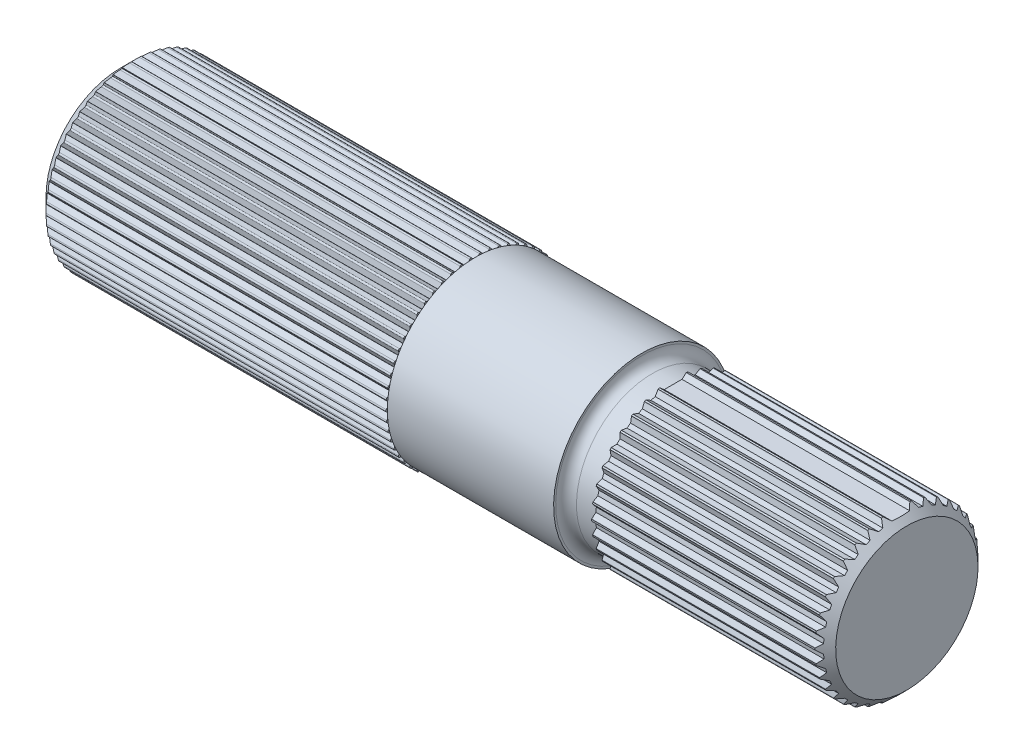
SolidWorks part; units mm, degrees
material "1.0725 (15SMn13)"
ref_plane "Ön Düzlem" through (0, 0, 0) normal (0, 0, 1) x (1, 0, 0)
ref_plane "Üst Düzlem" through (0, 0, 0) normal (0, 1, 0) x (1, 0, 0)
ref_plane "Sağ Düzlem" through (0, 0, 0) normal (1, 0, 0) x (0, 0, -1)
sketch "Çizim1" plane through (0, 0, 0) normal (0, 0, 1) x (1, 0, 0)
  line L0 (0, 0) -> (75.7, 0)
  line L1 (53.2, -7.3) -> (53.2, -7.85)
  line L2 (53.2, -7.85) -> (74.7, -7.85)
  line L3 (74.7, -7.85) -> (75.7, -6.85)
  line L4 (75.7, -6.85) -> (75.7, 0)
  line L5 (0, 0) -> (0, -7.16)
  line L6 (0, -7.16) -> (1.5, -8.66)
  line L7 (1.5, -8.66) -> (34.2, -8.66)
  line L8 (34.2, -8.66) -> (34.2, -8.5)
  line L9 (34.2, -8.5) -> (50.2, -8.5)
  line L10 (50.2, -8.5) -> (50.2, -8.3)
  line L11 (51.2, -7.3) -> (53.2, -7.3)
  arc A0 (51.2, -7.3) -> (50.2, -8.3) centre (51.2, -8.3) ccw
revolve "Döndür1" add sketch "Çizim1" angle 360 about L0
sketch "Çizim2" plane through (75.7, 0, 0) normal (1, 0, 0) x (0, 0, -1)
  line L0 (5.9329, 5.1084) -> (5.4037, 5.1084)
  line L1 (5.1084, 5.9329) -> (5.1084, 5.4037)
  line L2 (6.7298, 4.0006) -> (6.2087, 4.0925)
  line L3 (6.061, 4.9557) -> (5.9692, 4.4346)
  line L4 (7.6922, 1.4576) -> (7.234, 1.7221)
  line L5 (7.3904, 2.5838) -> (7.1259, 2.1256)
  line L6 (7.3222, 2.7712) -> (6.825, 2.9521)
  line L7 (6.8295, 3.8279) -> (6.6485, 3.3307)
  line L8 (7.8285, 0.0997) -> (7.4231, 0.4398)
  line L9 (7.7268, -1.2612) -> (7.3867, -0.8559)
  line L10 (7.8285, -0.0997) -> (7.4231, -0.4398)
  line L11 (6.8295, -3.8279) -> (6.6485, -3.3307)
  line L12 (6.7298, -4.0006) -> (6.2087, -4.0925)
  line L13 (7.3222, -2.7712) -> (6.825, -2.9521)
  line L14 (7.3904, -2.5838) -> (7.1259, -2.1256)
  line L15 (7.6922, -1.4576) -> (7.234, -1.7221)
  line L16 (6.061, -4.9557) -> (5.9692, -4.4346)
  line L17 (5.9329, -5.1084) -> (5.4037, -5.1084)
  line L18 (5.1084, -5.9329) -> (5.1084, -5.4037)
  line L19 (7.7268, 1.2612) -> (7.3867, 0.8559)
  line L20 (3.8279, 6.8295) -> (3.3307, 6.6485)
  line L21 (2.5838, 7.3904) -> (2.1256, 7.1259)
  line L22 (1.2612, 7.7268) -> (0.8559, 7.3867)
  line L23 (1.4576, 7.6922) -> (1.7221, 7.234)
  line L24 (2.7712, 7.3222) -> (2.9521, 6.825)
  line L25 (-1.2612, 7.7268) -> (-0.8559, 7.3867)
  line L26 (-2.5838, 7.3904) -> (-2.1256, 7.1259)
  line L27 (-2.7712, 7.3222) -> (-2.9521, 6.825)
  line L28 (-1.4576, 7.6922) -> (-1.7221, 7.234)
  line L29 (-0.8559, 7.3867) -> (0.8559, 7.3867)
  line L30 (4.9557, 6.061) -> (4.4346, 5.9692)
  line L31 (4.0006, 6.7298) -> (4.0925, 6.2087)
  line L32 (-5.9329, 5.1084) -> (-5.4037, 5.1084)
  line L33 (-5.1084, 5.9329) -> (-5.1084, 5.4037)
  line L34 (-4.9557, 6.061) -> (-4.4346, 5.9692)
  line L35 (-6.7298, 4.0006) -> (-6.2087, 4.0925)
  line L36 (-6.061, 4.9557) -> (-5.9692, 4.4346)
  line L37 (-7.3222, 2.7712) -> (-6.825, 2.9521)
  line L38 (-7.6922, 1.4576) -> (-7.234, 1.7221)
  line L39 (-7.3904, 2.5838) -> (-7.1259, 2.1256)
  line L40 (-6.8295, 3.8279) -> (-6.6485, 3.3307)
  line L41 (-4.0006, 6.7298) -> (-4.0925, 6.2087)
  line L42 (-3.8279, 6.8295) -> (-3.3307, 6.6485)
  line L43 (4.9557, -6.061) -> (4.4346, -5.9692)
  line L44 (2.5838, -7.3904) -> (2.1256, -7.1259)
  line L45 (1.2612, -7.7268) -> (0.8559, -7.3867)
  line L46 (1.4576, -7.6922) -> (1.7221, -7.234)
  line L47 (2.7712, -7.3222) -> (2.9521, -6.825)
  line L48 (4.0006, -6.7298) -> (4.0925, -6.2087)
  line L49 (3.8279, -6.8295) -> (3.3307, -6.6485)
  line L50 (0.0997, -7.8285) -> (0.4398, -7.4231)
  line L51 (-0.0997, -7.8285) -> (-0.4398, -7.4231)
  line L52 (-1.2612, -7.7268) -> (-0.8559, -7.3867)
  line L53 (-2.5838, -7.3904) -> (-2.1256, -7.1259)
  line L54 (-2.7712, -7.3222) -> (-2.9521, -6.825)
  line L55 (-1.4576, -7.6922) -> (-1.7221, -7.234)
  line L56 (-7.8285, 0.0997) -> (-7.4231, 0.4398)
  line L57 (-7.7268, -1.2612) -> (-7.3867, -0.8559)
  line L58 (-7.8285, -0.0997) -> (-7.4231, -0.4398)
  line L59 (-7.3904, -2.5838) -> (-7.1259, -2.1256)
  line L60 (-6.8295, -3.8279) -> (-6.6485, -3.3307)
  line L61 (-6.7298, -4.0006) -> (-6.2087, -4.0925)
  line L62 (-7.3222, -2.7712) -> (-6.825, -2.9521)
  line L63 (-7.6922, -1.4576) -> (-7.234, -1.7221)
  line L64 (-5.9329, -5.1084) -> (-5.4037, -5.1084)
  line L65 (-4.9557, -6.061) -> (-4.4346, -5.9692)
  line L66 (-5.1084, -5.9329) -> (-5.1084, -5.4037)
  line L67 (-6.061, -4.9557) -> (-5.9692, -4.4346)
  line L68 (-4.0006, -6.7298) -> (-4.0925, -6.2087)
  line L69 (-3.8279, -6.8295) -> (-3.3307, -6.6485)
  line L70 (4.0811, -6.273) -> (-4.0811, -6.273) construction
  line L71 (-7.7268, 1.2612) -> (-7.3867, 0.8559)
  arc A0 (5.4037, 5.1084) -> (5.1084, 5.4037) centre (0, 0) ccw
  arc A1 (6.8295, 3.8279) -> (6.7298, 4.0006) centre (6.7072, 3.8724) ccw
  arc A2 (6.2087, 4.0925) -> (5.9692, 4.4346) centre (0, 0) ccw
  arc A3 (6.061, 4.9557) -> (5.9329, 5.1084) centre (5.9329, 4.9783) ccw
  arc A4 (7.3904, 2.5838) -> (7.3222, 2.7712) centre (7.2777, 2.6489) ccw
  arc A5 (7.7268, 1.2612) -> (7.6922, 1.4576) centre (7.6271, 1.3449) ccw
  arc A6 (6.825, 2.9521) -> (6.6485, 3.3307) centre (0, 0) ccw
  arc A7 (7.234, 1.7221) -> (7.1259, 2.1256) centre (0, 0) ccw
  arc A8 (7.8285, -0.0997) -> (7.8285, 0.0997) centre (7.7448, 0) ccw
  arc A9 (7.4231, 0.4398) -> (7.3867, 0.8559) centre (0, 0) ccw
  arc A10 (7.3867, -0.8559) -> (7.4231, -0.4398) centre (0, 0) ccw
  arc A11 (7.6922, -1.4576) -> (7.7268, -1.2612) centre (7.6271, -1.3449) ccw
  arc A12 (7.3222, -2.7712) -> (7.3904, -2.5838) centre (7.2777, -2.6489) ccw
  arc A13 (7.1259, -2.1256) -> (7.234, -1.7221) centre (0, 0) ccw
  arc A14 (6.7298, -4.0006) -> (6.8295, -3.8279) centre (6.7072, -3.8724) ccw
  arc A15 (6.6485, -3.3307) -> (6.825, -2.9521) centre (0, 0) ccw
  arc A16 (5.1084, -5.4037) -> (5.4037, -5.1084) centre (0, 0) ccw
  arc A17 (5.9329, -5.1084) -> (6.061, -4.9557) centre (5.9329, -4.9783) ccw
  arc A18 (5.9692, -4.4346) -> (6.2087, -4.0925) centre (0, 0) ccw
  arc A19 (3.3307, 6.6485) -> (2.9521, 6.825) centre (0, 0) ccw
  arc A20 (4.0006, 6.7298) -> (3.8279, 6.8295) centre (3.8724, 6.7072) ccw
  arc A21 (1.4576, 7.6922) -> (1.2612, 7.7268) centre (1.3449, 7.6271) ccw
  arc A22 (2.7712, 7.3222) -> (2.5838, 7.3904) centre (2.6489, 7.2777) ccw
  arc A23 (2.1256, 7.1259) -> (1.7221, 7.234) centre (0, 0) ccw
  arc A24 (-1.2612, 7.7268) -> (-1.4576, 7.6922) centre (-1.3449, 7.6271) ccw
  arc A25 (-1.7221, 7.234) -> (-2.1256, 7.1259) centre (0, 0) ccw
  arc A26 (-2.9521, 6.825) -> (-3.3307, 6.6485) centre (0, 0) ccw
  arc A27 (-2.5838, 7.3904) -> (-2.7712, 7.3222) centre (-2.6489, 7.2777) ccw
  arc A28 (4.4346, 5.9692) -> (4.0925, 6.2087) centre (0, 0) ccw
  arc A29 (-3.8279, 6.8295) -> (-4.0006, 6.7298) centre (-3.8724, 6.7072) ccw
  arc A30 (-4.0925, 6.2087) -> (-4.4346, 5.9692) centre (0, 0) ccw
  arc A31 (-5.1084, 5.4037) -> (-5.4037, 5.1084) centre (0, 0) ccw
  arc A32 (-4.9557, 6.061) -> (-5.1084, 5.9329) centre (-4.9783, 5.9329) ccw
  arc A33 (-6.7298, 4.0006) -> (-6.8295, 3.8279) centre (-6.7072, 3.8724) ccw
  arc A34 (-5.9329, 5.1084) -> (-6.061, 4.9557) centre (-5.9329, 4.9783) ccw
  arc A35 (-5.9692, 4.4346) -> (-6.2087, 4.0925) centre (0, 0) ccw
  arc A36 (-6.6485, 3.3307) -> (-6.825, 2.9521) centre (0, 0) ccw
  arc A37 (-7.3222, 2.7712) -> (-7.3904, 2.5838) centre (-7.2777, 2.6489) ccw
  arc A38 (-7.1259, 2.1256) -> (-7.234, 1.7221) centre (0, 0) ccw
  arc A39 (-7.6922, 1.4576) -> (-7.7268, 1.2612) centre (-7.6271, 1.3449) ccw
  arc A40 (4.0925, -6.2087) -> (4.4346, -5.9692) centre (0, 0) ccw
  arc A41 (3.8279, -6.8295) -> (4.0006, -6.7298) centre (3.8724, -6.7072) ccw
  arc A42 (2.5838, -7.3904) -> (2.7712, -7.3222) centre (2.6489, -7.2777) ccw
  arc A43 (1.2612, -7.7268) -> (1.4576, -7.6922) centre (1.3449, -7.6271) ccw
  arc A44 (1.7221, -7.234) -> (2.1256, -7.1259) centre (0, 0) ccw
  arc A45 (2.9521, -6.825) -> (3.3307, -6.6485) centre (0, 0) ccw
  arc A46 (-0.0997, -7.8285) -> (0.0997, -7.8285) centre (0, -7.7448) ccw
  arc A47 (-1.4576, -7.6922) -> (-1.2612, -7.7268) centre (-1.3449, -7.6271) ccw
  arc A48 (-0.8559, -7.3867) -> (-0.4398, -7.4231) centre (0, 0) ccw
  arc A49 (-2.1256, -7.1259) -> (-1.7221, -7.234) centre (0, 0) ccw
  arc A50 (-2.7712, -7.3222) -> (-2.5838, -7.3904) centre (-2.6489, -7.2777) ccw
  arc A51 (-3.3307, -6.6485) -> (-2.9521, -6.825) centre (0, 0) ccw
  arc A52 (0.4398, -7.4231) -> (0.8559, -7.3867) centre (0, 0) ccw
  arc A53 (-7.8285, 0.0997) -> (-7.8285, -0.0997) centre (-7.7448, 0) ccw
  arc A54 (-7.3867, 0.8559) -> (-7.4231, 0.4398) centre (0, 0) ccw
  arc A55 (-7.4231, -0.4398) -> (-7.3867, -0.8559) centre (0, 0) ccw
  arc A56 (-7.7268, -1.2612) -> (-7.6922, -1.4576) centre (-7.6271, -1.3449) ccw
  arc A57 (-7.3904, -2.5838) -> (-7.3222, -2.7712) centre (-7.2777, -2.6489) ccw
  arc A58 (-7.234, -1.7221) -> (-7.1259, -2.1256) centre (0, 0) ccw
  arc A59 (-6.825, -2.9521) -> (-6.6485, -3.3307) centre (0, 0) ccw
  arc A60 (-6.8295, -3.8279) -> (-6.7298, -4.0006) centre (-6.7072, -3.8724) ccw
  arc A61 (-5.4037, -5.1084) -> (-5.1084, -5.4037) centre (0, 0) ccw
  arc A62 (-4.4346, -5.9692) -> (-4.0925, -6.2087) centre (0, 0) ccw
  arc A63 (-5.1084, -5.9329) -> (-4.9557, -6.061) centre (-4.9783, -5.9329) ccw
  arc A64 (-6.061, -4.9557) -> (-5.9329, -5.1084) centre (-5.9329, -4.9783) ccw
  arc A65 (-4.0006, -6.7298) -> (-3.8279, -6.8295) centre (-3.8724, -6.7072) ccw
  arc A66 (-6.2087, -4.0925) -> (-5.9692, -4.4346) centre (0, 0) ccw
  arc A67 (4.9557, -6.061) -> (5.1084, -5.9329) centre (4.9783, -5.9329) ccw
  arc A68 (5.1084, 5.9329) -> (4.9557, 6.061) centre (4.9783, 5.9329) ccw
extrude "Kes-Ekstrüzyon1" cut sketch "Çizim2" against normal blind 23 flip side to cut
sketch "Çizim4" plane through (0, 0, 0) normal (-1, 0, 0) x (0, 0, 1)
  line L0 (-0.3668, 8.6063) -> (-0.0052, 8.22)
  line L1 (0.3668, 8.6063) -> (0.0052, 8.22)
  line L2 (1.2951, 8.5162) -> (0.8939, 8.1712)
  line L3 (0.5659, 8.5955) -> (0.8835, 8.1723)
  line L4 (2.2083, 8.3262) -> (1.7721, 8.0267)
  line L5 (1.4919, 8.4839) -> (1.762, 8.0289)
  line L6 (3.0956, 8.0387) -> (2.6296, 7.788)
  line L7 (2.4004, 8.2729) -> (2.6197, 7.7913)
  line L8 (3.9465, 7.6568) -> (3.4562, 7.458)
  line L9 (3.2808, 7.9648) -> (3.4467, 7.4624)
  line L10 (4.7513, 7.1853) -> (4.2423, 7.0406)
  line L11 (4.1227, 7.5634) -> (4.2334, 7.046)
  line L12 (5.5003, 6.6294) -> (4.9787, 6.5407)
  line L13 (4.9163, 7.0733) -> (4.9704, 6.547)
  line L14 (6.1848, 5.9959) -> (5.6566, 5.9641)
  line L15 (5.6523, 6.5003) -> (5.6491, 5.9712)
  line L16 (6.7968, 5.292) -> (6.2683, 5.3175)
  line L17 (6.3219, 5.8511) -> (6.2616, 5.3255)
  line L18 (7.3291, 4.5262) -> (6.8065, 4.6086)
  line L19 (6.9175, 5.1333) -> (6.8006, 4.6173)
  line L20 (7.7755, 3.7072) -> (7.2649, 3.8457)
  line L21 (7.4319, 4.3553) -> (7.26, 3.8549)
  line L22 (8.1308, 2.8448) -> (7.6381, 3.0377)
  line L23 (7.8593, 3.5262) -> (7.6342, 3.0474)
  line L24 (8.3907, 1.949) -> (7.9217, 2.194)
  line L25 (8.1945, 2.6558) -> (7.9189, 2.2041)
  line L26 (8.5522, 1.0304) -> (8.1125, 1.3247)
  line L27 (8.4336, 1.7543) -> (8.1108, 1.335)
  line L28 (8.6135, 0.0997) -> (8.2082, 0.4398)
  line L29 (8.5738, 0.8322) -> (8.2076, 0.4502)
  line L30 (8.5738, -0.8322) -> (8.2076, -0.4502)
  line L31 (8.6135, -0.0997) -> (8.2082, -0.4398)
  line L32 (8.4336, -1.7543) -> (8.1108, -1.335)
  line L33 (8.5522, -1.0304) -> (8.1125, -1.3247)
  line L34 (8.1945, -2.6558) -> (7.9189, -2.2041)
  line L35 (8.3907, -1.949) -> (7.9217, -2.194)
  line L36 (7.8593, -3.5262) -> (7.6342, -3.0474)
  line L37 (8.1308, -2.8448) -> (7.6381, -3.0377)
  line L38 (7.4319, -4.3553) -> (7.26, -3.8549)
  line L39 (7.7755, -3.7072) -> (7.2649, -3.8457)
  line L40 (6.9175, -5.1333) -> (6.8006, -4.6173)
  line L41 (7.3291, -4.5262) -> (6.8065, -4.6086)
  line L42 (6.3219, -5.8511) -> (6.2616, -5.3255)
  line L43 (6.7968, -5.292) -> (6.2683, -5.3175)
  line L44 (5.6523, -6.5003) -> (5.6491, -5.9712)
  line L45 (6.1848, -5.9959) -> (5.6566, -5.9641)
  line L46 (4.9163, -7.0733) -> (4.9704, -6.547)
  line L47 (5.5003, -6.6294) -> (4.9787, -6.5407)
  line L48 (4.1227, -7.5634) -> (4.2334, -7.046)
  line L49 (4.7513, -7.1853) -> (4.2423, -7.0406)
  line L50 (3.2808, -7.9648) -> (3.4467, -7.4624)
  line L51 (3.9465, -7.6568) -> (3.4562, -7.458)
  line L52 (2.4004, -8.2729) -> (2.6197, -7.7913)
  line L53 (3.0956, -8.0387) -> (2.6296, -7.788)
  line L54 (1.4919, -8.4839) -> (1.762, -8.0289)
  line L55 (2.2083, -8.3262) -> (1.7721, -8.0267)
  line L56 (0.5659, -8.5955) -> (0.8835, -8.1723)
  line L57 (1.2951, -8.5162) -> (0.8939, -8.1712)
  line L58 (-0.3668, -8.6063) -> (-0.0052, -8.22)
  line L59 (0.3668, -8.6063) -> (0.0052, -8.22)
  line L60 (-1.2951, -8.5162) -> (-0.8939, -8.1712)
  line L61 (-0.5659, -8.5955) -> (-0.8835, -8.1723)
  line L62 (-2.2083, -8.3262) -> (-1.7721, -8.0267)
  line L63 (-1.4919, -8.4839) -> (-1.762, -8.0289)
  line L64 (-3.0956, -8.0387) -> (-2.6296, -7.788)
  line L65 (-2.4004, -8.2729) -> (-2.6197, -7.7913)
  line L66 (-3.9465, -7.6568) -> (-3.4562, -7.458)
  line L67 (-3.2808, -7.9648) -> (-3.4467, -7.4624)
  line L68 (-4.7513, -7.1853) -> (-4.2423, -7.0406)
  line L69 (-4.1227, -7.5634) -> (-4.2334, -7.046)
  line L70 (-5.5003, -6.6294) -> (-4.9787, -6.5407)
  line L71 (-4.9163, -7.0733) -> (-4.9704, -6.547)
  line L72 (-6.1848, -5.9959) -> (-5.6566, -5.9641)
  line L73 (-5.6523, -6.5003) -> (-5.6491, -5.9712)
  line L74 (-6.7968, -5.292) -> (-6.2683, -5.3175)
  line L75 (-6.3219, -5.8511) -> (-6.2616, -5.3255)
  line L76 (-7.3291, -4.5262) -> (-6.8065, -4.6086)
  line L77 (-6.9175, -5.1333) -> (-6.8006, -4.6173)
  line L78 (-7.7755, -3.7072) -> (-7.2649, -3.8457)
  line L79 (-7.4319, -4.3553) -> (-7.26, -3.8549)
  line L80 (-8.1308, -2.8448) -> (-7.6381, -3.0377)
  line L81 (-7.8593, -3.5262) -> (-7.6342, -3.0474)
  line L82 (-8.3907, -1.949) -> (-7.9217, -2.194)
  line L83 (-8.1945, -2.6558) -> (-7.9189, -2.2041)
  line L84 (-8.5522, -1.0304) -> (-8.1125, -1.3247)
  line L85 (-8.4336, -1.7543) -> (-8.1108, -1.335)
  line L86 (-8.6135, -0.0997) -> (-8.2082, -0.4398)
  line L87 (-8.5738, -0.8322) -> (-8.2076, -0.4502)
  line L88 (-8.5738, 0.8322) -> (-8.2076, 0.4502)
  line L89 (-8.6135, 0.0997) -> (-8.2082, 0.4398)
  line L90 (-8.4336, 1.7543) -> (-8.1108, 1.335)
  line L91 (-8.5522, 1.0304) -> (-8.1125, 1.3247)
  line L92 (-8.1945, 2.6558) -> (-7.9189, 2.2041)
  line L93 (-8.3907, 1.949) -> (-7.9217, 2.194)
  line L94 (-7.8593, 3.5262) -> (-7.6342, 3.0474)
  line L95 (-8.1308, 2.8448) -> (-7.6381, 3.0377)
  line L96 (-7.4319, 4.3553) -> (-7.26, 3.8549)
  line L97 (-7.7755, 3.7072) -> (-7.2649, 3.8457)
  line L98 (-6.9175, 5.1333) -> (-6.8006, 4.6173)
  line L99 (-7.3291, 4.5262) -> (-6.8065, 4.6086)
  line L100 (-6.3219, 5.8511) -> (-6.2616, 5.3255)
  line L101 (-6.7968, 5.292) -> (-6.2683, 5.3175)
  line L102 (-5.6523, 6.5003) -> (-5.6491, 5.9712)
  line L103 (-6.1848, 5.9959) -> (-5.6566, 5.9641)
  line L104 (-4.9163, 7.0733) -> (-4.9704, 6.547)
  line L105 (-5.5003, 6.6294) -> (-4.9787, 6.5407)
  line L106 (-4.1227, 7.5634) -> (-4.2334, 7.046)
  line L107 (-4.7513, 7.1853) -> (-4.2423, 7.0406)
  line L108 (-3.2808, 7.9648) -> (-3.4467, 7.4624)
  line L109 (-3.9465, 7.6568) -> (-3.4562, 7.458)
  line L110 (-2.4004, 8.2729) -> (-2.6197, 7.7913)
  line L111 (-3.0956, 8.0387) -> (-2.6296, 7.788)
  line L112 (-1.4919, 8.4839) -> (-1.762, 8.0289)
  line L113 (-2.2083, 8.3262) -> (-1.7721, 8.0267)
  line L114 (-0.5659, 8.5955) -> (-0.8835, 8.1723)
  line L115 (-1.2951, 8.5162) -> (-0.8939, 8.1712)
  arc A0 (0.0052, 8.22) -> (-0.0052, 8.22) centre (0, 0) ccw
  arc A1 (0.5659, 8.5955) -> (0.3668, 8.6063) centre (0.4618, 8.5173) ccw
  arc A2 (1.4919, 8.4839) -> (1.2951, 8.5162) centre (1.38, 8.4175) ccw
  arc A3 (0.8939, 8.1712) -> (0.8835, 8.1723) centre (0, 0) ccw
  arc A4 (2.4004, 8.2729) -> (2.2083, 8.3262) centre (2.282, 8.2189) ccw
  arc A5 (1.7721, 8.0267) -> (1.762, 8.0289) centre (0, 0) ccw
  arc A6 (3.2808, 7.9648) -> (3.0956, 8.0387) centre (3.1572, 7.924) ccw
  arc A7 (2.6296, 7.788) -> (2.6197, 7.7913) centre (0, 0) ccw
  arc A8 (4.1227, 7.5634) -> (3.9465, 7.6568) centre (3.9954, 7.5362) ccw
  arc A9 (3.4562, 7.458) -> (3.4467, 7.4624) centre (0, 0) ccw
  arc A10 (4.9163, 7.0733) -> (4.7513, 7.1853) centre (4.7868, 7.0601) ccw
  arc A11 (4.2423, 7.0406) -> (4.2334, 7.046) centre (0, 0) ccw
  arc A12 (5.6523, 6.5003) -> (5.5003, 6.6294) centre (5.5221, 6.5011) ccw
  arc A13 (4.9787, 6.5407) -> (4.9704, 6.547) centre (0, 0) ccw
  arc A14 (6.3219, 5.8511) -> (6.1848, 5.9959) centre (6.1926, 5.866) ccw
  arc A15 (5.6566, 5.9641) -> (5.6491, 5.9712) centre (0, 0) ccw
  arc A16 (6.9175, 5.1333) -> (6.7968, 5.292) centre (6.7905, 5.162) ccw
  arc A17 (6.2683, 5.3175) -> (6.2616, 5.3255) centre (0, 0) ccw
  arc A18 (7.4319, 4.3553) -> (7.3291, 4.5262) centre (7.3089, 4.3976) ccw
  arc A19 (6.8065, 4.6086) -> (6.8006, 4.6173) centre (0, 0) ccw
  arc A20 (7.8593, 3.5262) -> (7.7755, 3.7072) centre (7.7415, 3.5816) ccw
  arc A21 (7.2649, 3.8457) -> (7.26, 3.8549) centre (0, 0) ccw
  arc A22 (8.1945, 2.6558) -> (8.1308, 2.8448) centre (8.0833, 2.7236) ccw
  arc A23 (7.6381, 3.0377) -> (7.6342, 3.0474) centre (0, 0) ccw
  arc A24 (8.4336, 1.7543) -> (8.3907, 1.949) centre (8.3304, 1.8337) ccw
  arc A25 (7.9217, 2.194) -> (7.9189, 2.2041) centre (0, 0) ccw
  arc A26 (8.5738, 0.8322) -> (8.5522, 1.0304) centre (8.4798, 0.9222) ccw
  arc A27 (8.1125, 1.3247) -> (8.1108, 1.335) centre (0, 0) ccw
  arc A28 (8.6135, -0.0997) -> (8.6135, 0.0997) centre (8.5298, 0) ccw
  arc A29 (8.2082, 0.4398) -> (8.2076, 0.4502) centre (0, 0) ccw
  arc A30 (8.5522, -1.0304) -> (8.5738, -0.8322) centre (8.4798, -0.9222) ccw
  arc A31 (8.2076, -0.4502) -> (8.2082, -0.4398) centre (0, 0) ccw
  arc A32 (8.3907, -1.949) -> (8.4336, -1.7543) centre (8.3304, -1.8337) ccw
  arc A33 (8.1108, -1.335) -> (8.1125, -1.3247) centre (0, 0) ccw
  arc A34 (8.1308, -2.8448) -> (8.1945, -2.6558) centre (8.0833, -2.7236) ccw
  arc A35 (7.9189, -2.2041) -> (7.9217, -2.194) centre (0, 0) ccw
  arc A36 (7.7755, -3.7072) -> (7.8593, -3.5262) centre (7.7415, -3.5816) ccw
  arc A37 (7.6342, -3.0474) -> (7.6381, -3.0377) centre (0, 0) ccw
  arc A38 (7.3291, -4.5262) -> (7.4319, -4.3553) centre (7.3089, -4.3976) ccw
  arc A39 (7.26, -3.8549) -> (7.2649, -3.8457) centre (0, 0) ccw
  arc A40 (6.7968, -5.292) -> (6.9175, -5.1333) centre (6.7905, -5.162) ccw
  arc A41 (6.8006, -4.6173) -> (6.8065, -4.6086) centre (0, 0) ccw
  arc A42 (6.1848, -5.9959) -> (6.3219, -5.8511) centre (6.1926, -5.866) ccw
  arc A43 (6.2616, -5.3255) -> (6.2683, -5.3175) centre (0, 0) ccw
  arc A44 (5.5003, -6.6294) -> (5.6523, -6.5003) centre (5.5221, -6.5011) ccw
  arc A45 (5.6491, -5.9712) -> (5.6566, -5.9641) centre (0, 0) ccw
  arc A46 (4.7513, -7.1853) -> (4.9163, -7.0733) centre (4.7868, -7.0601) ccw
  arc A47 (4.9704, -6.547) -> (4.9787, -6.5407) centre (0, 0) ccw
  arc A48 (3.9465, -7.6568) -> (4.1227, -7.5634) centre (3.9954, -7.5362) ccw
  arc A49 (4.2334, -7.046) -> (4.2423, -7.0406) centre (0, 0) ccw
  arc A50 (3.0956, -8.0387) -> (3.2808, -7.9648) centre (3.1572, -7.924) ccw
  arc A51 (3.4467, -7.4624) -> (3.4562, -7.458) centre (0, 0) ccw
  arc A52 (2.2083, -8.3262) -> (2.4004, -8.2729) centre (2.282, -8.2189) ccw
  arc A53 (2.6197, -7.7913) -> (2.6296, -7.788) centre (0, 0) ccw
  arc A54 (1.2951, -8.5162) -> (1.4919, -8.4839) centre (1.38, -8.4175) ccw
  arc A55 (1.762, -8.0289) -> (1.7721, -8.0267) centre (0, 0) ccw
  arc A56 (0.3668, -8.6063) -> (0.5659, -8.5955) centre (0.4618, -8.5173) ccw
  arc A57 (0.8835, -8.1723) -> (0.8939, -8.1712) centre (0, 0) ccw
  arc A58 (-0.5659, -8.5955) -> (-0.3668, -8.6063) centre (-0.4618, -8.5173) ccw
  arc A60 (-0.0052, -8.22) -> (0.0052, -8.22) centre (0, 0) ccw
  arc A61 (-1.4919, -8.4839) -> (-1.2951, -8.5162) centre (-1.38, -8.4175) ccw
  arc A62 (-0.8939, -8.1712) -> (-0.8835, -8.1723) centre (0, 0) ccw
  arc A63 (-2.4004, -8.2729) -> (-2.2083, -8.3262) centre (-2.282, -8.2189) ccw
  arc A64 (-1.7721, -8.0267) -> (-1.762, -8.0289) centre (0, 0) ccw
  arc A65 (-3.2808, -7.9648) -> (-3.0956, -8.0387) centre (-3.1572, -7.924) ccw
  arc A66 (-2.6296, -7.788) -> (-2.6197, -7.7913) centre (0, 0) ccw
  arc A67 (-4.1227, -7.5634) -> (-3.9465, -7.6568) centre (-3.9954, -7.5362) ccw
  arc A68 (-3.4562, -7.458) -> (-3.4467, -7.4624) centre (0, 0) ccw
  arc A69 (-4.9163, -7.0733) -> (-4.7513, -7.1853) centre (-4.7868, -7.0601) ccw
  arc A70 (-4.2423, -7.0406) -> (-4.2334, -7.046) centre (0, 0) ccw
  arc A71 (-5.6523, -6.5003) -> (-5.5003, -6.6294) centre (-5.5221, -6.5011) ccw
  arc A72 (-4.9787, -6.5407) -> (-4.9704, -6.547) centre (0, 0) ccw
  arc A73 (-6.3219, -5.8511) -> (-6.1848, -5.9959) centre (-6.1926, -5.866) ccw
  arc A74 (-5.6566, -5.9641) -> (-5.6491, -5.9712) centre (0, 0) ccw
  arc A75 (-6.9175, -5.1333) -> (-6.7968, -5.292) centre (-6.7905, -5.162) ccw
  arc A76 (-6.2683, -5.3175) -> (-6.2616, -5.3255) centre (0, 0) ccw
  arc A77 (-7.4319, -4.3553) -> (-7.3291, -4.5262) centre (-7.3089, -4.3976) ccw
  arc A78 (-6.8065, -4.6086) -> (-6.8006, -4.6173) centre (0, 0) ccw
  arc A79 (-7.8593, -3.5262) -> (-7.7755, -3.7072) centre (-7.7415, -3.5816) ccw
  arc A80 (-7.2649, -3.8457) -> (-7.26, -3.8549) centre (0, 0) ccw
  arc A81 (-8.1945, -2.6558) -> (-8.1308, -2.8448) centre (-8.0833, -2.7236) ccw
  arc A82 (-7.6381, -3.0377) -> (-7.6342, -3.0474) centre (0, 0) ccw
  arc A83 (-8.4336, -1.7543) -> (-8.3907, -1.949) centre (-8.3304, -1.8337) ccw
  arc A84 (-7.9217, -2.194) -> (-7.9189, -2.2041) centre (0, 0) ccw
  arc A85 (-8.5738, -0.8322) -> (-8.5522, -1.0304) centre (-8.4798, -0.9222) ccw
  arc A86 (-8.1125, -1.3247) -> (-8.1108, -1.335) centre (0, 0) ccw
  arc A87 (-8.6135, 0.0997) -> (-8.6135, -0.0997) centre (-8.5298, 0) ccw
  arc A88 (-8.2082, -0.4398) -> (-8.2076, -0.4502) centre (0, 0) ccw
  arc A89 (-8.5522, 1.0304) -> (-8.5738, 0.8322) centre (-8.4798, 0.9222) ccw
  arc A90 (-8.2076, 0.4502) -> (-8.2082, 0.4398) centre (0, 0) ccw
  arc A91 (-8.3907, 1.949) -> (-8.4336, 1.7543) centre (-8.3304, 1.8337) ccw
  arc A92 (-8.1108, 1.335) -> (-8.1125, 1.3247) centre (0, 0) ccw
  arc A93 (-8.1308, 2.8448) -> (-8.1945, 2.6558) centre (-8.0833, 2.7236) ccw
  arc A94 (-7.9189, 2.2041) -> (-7.9217, 2.194) centre (0, 0) ccw
  arc A95 (-7.7755, 3.7072) -> (-7.8593, 3.5262) centre (-7.7415, 3.5816) ccw
  arc A96 (-7.6342, 3.0474) -> (-7.6381, 3.0377) centre (0, 0) ccw
  arc A97 (-7.3291, 4.5262) -> (-7.4319, 4.3553) centre (-7.3089, 4.3976) ccw
  arc A98 (-7.26, 3.8549) -> (-7.2649, 3.8457) centre (0, 0) ccw
  arc A99 (-6.7968, 5.292) -> (-6.9175, 5.1333) centre (-6.7905, 5.162) ccw
  arc A100 (-6.8006, 4.6173) -> (-6.8065, 4.6086) centre (0, 0) ccw
  arc A101 (-6.1848, 5.9959) -> (-6.3219, 5.8511) centre (-6.1926, 5.866) ccw
  arc A102 (-6.2616, 5.3255) -> (-6.2683, 5.3175) centre (0, 0) ccw
  arc A103 (-5.5003, 6.6294) -> (-5.6523, 6.5003) centre (-5.5221, 6.5011) ccw
  arc A104 (-5.6491, 5.9712) -> (-5.6566, 5.9641) centre (0, 0) ccw
  arc A105 (-4.7513, 7.1853) -> (-4.9163, 7.0733) centre (-4.7868, 7.0601) ccw
  arc A106 (-4.9704, 6.547) -> (-4.9787, 6.5407) centre (0, 0) ccw
  arc A107 (-3.9465, 7.6568) -> (-4.1227, 7.5634) centre (-3.9954, 7.5362) ccw
  arc A108 (-4.2334, 7.046) -> (-4.2423, 7.0406) centre (0, 0) ccw
  arc A109 (-3.0956, 8.0387) -> (-3.2808, 7.9648) centre (-3.1572, 7.924) ccw
  arc A110 (-3.4467, 7.4624) -> (-3.4562, 7.458) centre (0, 0) ccw
  arc A111 (-2.2083, 8.3262) -> (-2.4004, 8.2729) centre (-2.282, 8.2189) ccw
  arc A112 (-2.6197, 7.7913) -> (-2.6296, 7.788) centre (0, 0) ccw
  arc A113 (-1.2951, 8.5162) -> (-1.4919, 8.4839) centre (-1.38, 8.4175) ccw
  arc A114 (-1.762, 8.0289) -> (-1.7721, 8.0267) centre (0, 0) ccw
  arc A115 (-0.3668, 8.6063) -> (-0.5659, 8.5955) centre (-0.4618, 8.5173) ccw
  arc A116 (-0.8835, 8.1723) -> (-0.8939, 8.1712) centre (0, 0) ccw
  point P351 (0, 0)
extrude "Kes-Ekstrüzyon3" cut sketch "Çizim4" against normal up to surface (34.2 mm away) flip side to cut up to face at (34.2, -8.5, 0)
